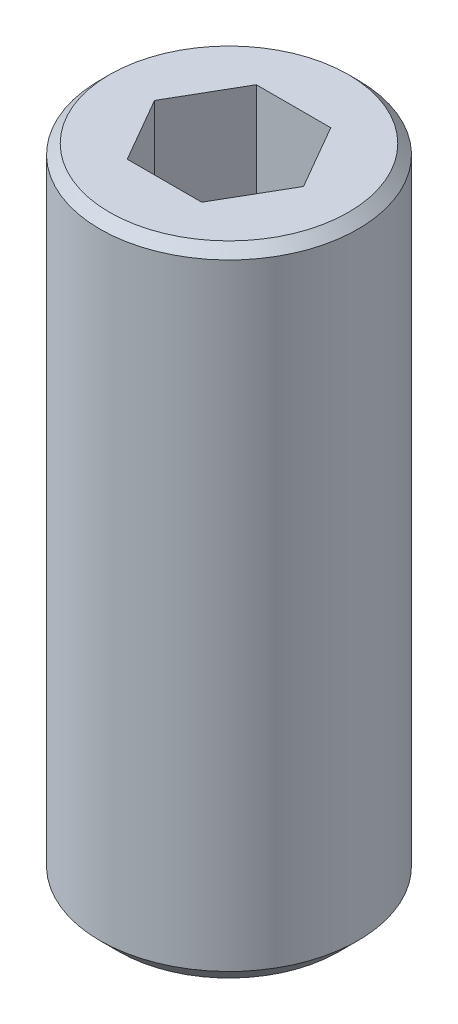
SolidWorks part; units mm, degrees
material "acero"
ref_plane "Alzado" through (0, 0, 0) normal (0, 0, 1) x (1, 0, 0)
ref_plane "Planta" through (0, 0, 0) normal (0, 1, 0) x (1, 0, 0)
ref_plane "Vista lateral" through (0, 0, 0) normal (1, 0, 0) x (0, 0, -1)
sketch "Croquis1" plane through (0, 0, 0) normal (0, 0, 1) x (1, 0, 0)
  line L0 (0, 0) -> (0, -60.9498) construction
  line L1 (0, 0) -> (2, 0)
  line L4 (2, 0) -> (2, -10)
  line L5 (2, -10) -> (0, -10)
  line L6 (0, -10) -> (0, 0)
  dimension "D1" = 10
  dimension "D4" = 4
revolve "Revolución1" add sketch "Croquis1" angle 360 about L0
cosmetic thread "Rosca cosmética1" parameters "D2"=3.22
sketch "Croquis3" plane through (0, 0, 0) normal (0, 1, 0) x (1, 0, 0)
  line L1 (-0.5774, 1) -> (-1.1547, 0)
  line L2 (-1.1547, 0) -> (-0.5774, -1)
  line L3 (-0.5774, -1) -> (0.5774, -1)
  line L4 (0.5774, -1) -> (1.1547, 0)
  line L5 (1.1547, 0) -> (0.5774, 1)
  line L6 (0.5774, 1) -> (-0.5774, 1)
  circle A0 centre (0, 0) radius 1 construction
  dimension "D1" = 2
extrude "Cortar-Extruir2" cut sketch "Croquis3" against normal blind 2
chamfer "Chaflán3" distance 0.3 angle 45
chamfer "Chaflán4" distance 0.15 angle 45
